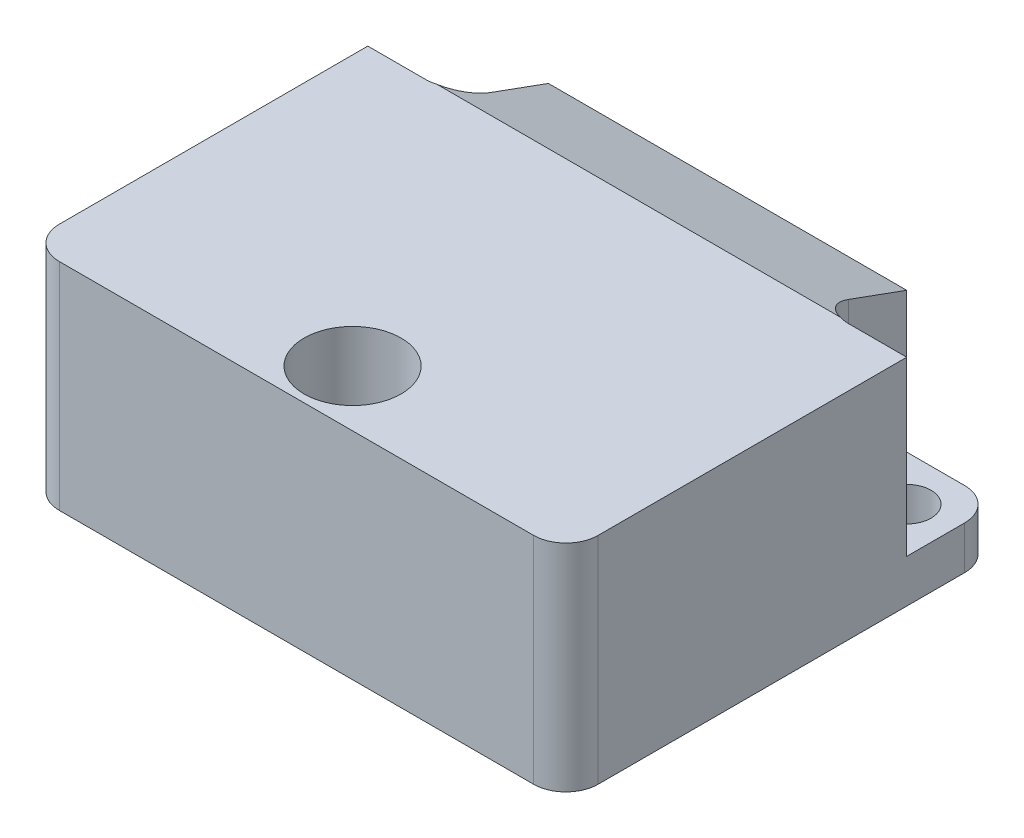
SolidWorks part; units mm, degrees
material "2014 Alloy"
ref_plane "Front Plane" through (0, 0, 0) normal (0, 0, 1) x (1, 0, 0)
ref_plane "Top Plane" through (0, 0, 0) normal (0, 1, 0) x (1, 0, 0)
ref_plane "Right Plane" through (0, 0, 0) normal (1, 0, 0) x (0, 0, -1)
sketch "Sketch1" plane through (0, 0, 0) normal (0, 1, 0) x (1, 0, 0)
  line L1 (-25, -20) -> (25, -20)
  line L2 (-25, -20) -> (-25, 20)
  line L3 (-25, 20) -> (25, 20)
  line L4 (25, -20) -> (25, 20)
  line L5 (-25, -20) -> (25, 20) construction
  line L6 (-25, 20) -> (25, -20) construction
  point P0 (0, 0)
extrude "Boss-Extrude1" add sketch "Sketch1" along normal blind 20
fillet "Fillet1" radius 3 4 edges at (-25, 10, -20) (25, 10, -20) (-25, 10, 20) (25, 10, 20)
sketch "Sketch2" plane through (0, 20, 0) normal (0, 1, 0) x (1, 0, 0)
  line L0 (0, 0) -> (0, 22.9069) construction
  line L1 (-31.6213, 26.6213) -> (-16.6213, 26.6213)
  line L2 (-31.6213, 26.6213) -> (-31.6213, 11.6213)
  line L3 (-31.6213, 11.6213) -> (-16.6213, 11.6213)
  line L4 (-16.6213, 26.6213) -> (-16.6213, 11.6213)
  line L5 (-31.6213, 26.6213) -> (-16.6213, 11.6213) construction
  line L6 (-31.6213, 11.6213) -> (-16.6213, 26.6213) construction
  line L7 (31.6213, 11.6213) -> (16.6213, 11.6213)
  line L8 (16.6213, 26.6213) -> (16.6213, 11.6213)
  line L9 (31.6213, 26.6213) -> (16.6213, 26.6213)
  line L10 (31.6213, 26.6213) -> (31.6213, 11.6213)
  arc A0 (-22, 20) -> (-25, 17) centre (-22, 17) ccw construction
  point P0 (-24.1213, 19.1213)
extrude "Cut-Extrude1" cut sketch "Sketch2" against normal blind 16
sketch "Sketch3" plane through (0, 4, 0) normal (0, 1, 0) x (1, 0, 0)
  line L0 (0, 0) -> (0, 17.9728) construction
  circle A0 centre (20.8107, 15.8107) radius 2.2526
  circle A1 centre (-20.8107, 15.8107) radius 2.2526
extrude "Cut-Extrude2" cut sketch "Sketch3" against normal blind 16
fillet "Fillet2" radius 3 2 edges at (-16.6213, 12, -11.6213) (16.6213, 12, -11.6213)
chamfer "Chamfer1" distance 3 angle 70 1 edges at (0, 20, -20)
sketch "Sketch4" plane through (0, 20, 0) normal (0, 1, 0) x (1, 0, 0)
  circle A0 centre (0, -14.7902) radius 4.5
extrude "Cut-Extrude3" cut sketch "Sketch4" against normal through all
sketch "Sketch5" plane through (0, 0, -20) normal (0, 0, -1) x (-1, 0, 0)
  line L0 (6.8747, 10.9711) -> (-6.8747, 10.9711)
  line L1 (-6.8747, 10.9711) -> (-8.3825, 9.4633)
  line L2 (-8.3825, 9.4633) -> (-7.6286, 8.7094)
  line L3 (-7.6286, 8.7094) -> (7.6286, 8.7094)
  line L4 (0, 0) -> (0, 18.2036) construction
  line L5 (8.3825, 9.4633) -> (7.6286, 8.7094)
  line L6 (6.8747, 10.9711) -> (8.3825, 9.4633)
  point P9 (0, 8.7094)
  point P10 (0, 10.9711)
extrude "Cut-Extrude4" cut sketch "Sketch5" against normal blind 5
sketch "Sketch6" plane through (0, 0, -20) normal (0, 0, -1) x (-1, 0, 0)
  line L0 (0, 0) -> (0, 16.3124) construction
  circle A0 centre (13.0082, 10.46) radius 1.7944
  circle A1 centre (-13.0082, 10.46) radius 1.7944
extrude "Cut-Extrude5" cut sketch "Sketch6" against normal blind 8
sketch "Sketch7" plane through (0, 0, -15) normal (0, 0, -1) x (-1, 0, 0)
  line L0 (0, 10.3578) -> (1, 10.3578) construction
  line L1 (0, 0) -> (0, 24.4904) construction
  line L2 (0, 10.3578) -> (-1, 10.3578) construction
  circle A0 centre (0, 10.3578) radius 0.3109
  circle A1 centre (1, 10.3578) radius 0.3109
  circle A2 centre (2, 10.3578) radius 0.3109
  circle A3 centre (3, 10.3578) radius 0.3109
  circle A4 centre (4, 10.3578) radius 0.3109
  circle A5 centre (5, 10.3578) radius 0.3109
  circle A6 centre (6, 10.3578) radius 0.3109
  circle A7 centre (1, 9.3578) radius 0.3109
  circle A8 centre (2, 9.3578) radius 0.3109
  circle A9 centre (3, 9.3578) radius 0.3109
  circle A10 centre (4, 9.3578) radius 0.3109
  circle A11 centre (5, 9.3578) radius 0.3109
  circle A12 centre (6, 9.3578) radius 0.3109
  circle A13 centre (0, 9.3578) radius 0.3109
  circle A14 centre (-6, 9.3578) radius 0.3109
  circle A15 centre (-5, 9.3578) radius 0.3109
  circle A16 centre (-4, 9.3578) radius 0.3109
  circle A17 centre (-3, 9.3578) radius 0.3109
  circle A18 centre (-2, 9.3578) radius 0.3109
  circle A19 centre (-1, 9.3578) radius 0.3109
  circle A20 centre (-6, 10.3578) radius 0.3109
  circle A21 centre (-5, 10.3578) radius 0.3109
  circle A22 centre (-4, 10.3578) radius 0.3109
  circle A23 centre (-3, 10.3578) radius 0.3109
  circle A24 centre (-2, 10.3578) radius 0.3109
  circle A25 centre (-1, 10.3578) radius 0.3109
  dimension "D1" = 7
  dimension "D2" = 2
extrude "Boss-Extrude2" add sketch "Sketch7" along normal blind 4.5
